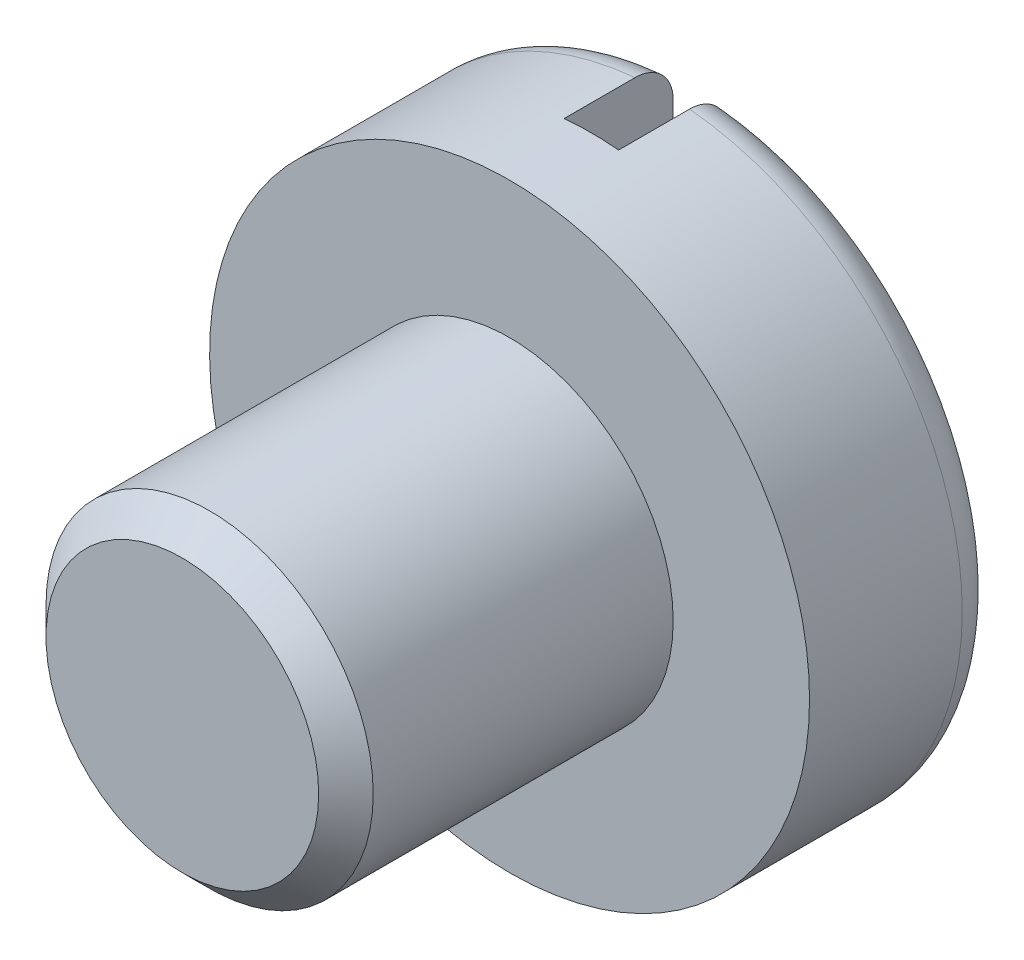
SolidWorks part; units mm, degrees
ref_plane "Plan de face" through (0, 0, 0) normal (0, 0, 1) x (1, 0, 0)
ref_plane "Plan de dessus" through (0, 0, 0) normal (0, 1, 0) x (1, 0, 0)
ref_plane "Plan de droite" through (0, 0, 0) normal (1, 0, 0) x (0, 0, -1)
sketch "Esquisse2" plane through (0, 0, 0) normal (0, 0, 1) x (1, 0, 0)
  circle A0 centre (0, 0) radius 5.5
  dimension "D1" = 11
extrude "Boss.-Extru.1" add sketch "Esquisse2" along normal blind 3.5
sketch "Esquisse3" plane through (0, 0, 3.5) normal (0, 0, 1) x (1, 0, 0)
  circle A0 centre (0, 0) radius 3
  dimension "D1" = 6
extrude "Boss.-Extru.2" add sketch "Esquisse3" along normal blind 6
fillet "Congé2" radius 0.7 1 edges at (5.5, 0, 0)
chamfer "Chanfrein1" distance 0.5 angle 45 1 edges at (3, 0, 9.5)
cosmetic thread "Représentation de filetage1" parameters "D2"=5
sketch "Esquisse4" plane through (0, 0, 0) normal (0, 0, -1) x (-1, 0, 0)
  line L0 (-0.5, 5.4772) -> (-0.5, -5.4772)
  line L1 (0.5, 5.4772) -> (0.5, -5.4772)
  circle A0 centre (0, 0) radius 5.5 construction
  arc A2 (-0.5, -5.4772) -> (0.5, -5.4772) centre (0, 0) ccw
  arc A3 (0.5, 5.4772) -> (-0.5, 5.4772) centre (0, 0) ccw
  dimension "D1" = 0.5
  dimension "D2" = 0.5
extrude "Enlèv. mat.-Extru.1" cut sketch "Esquisse4" against normal blind 2
